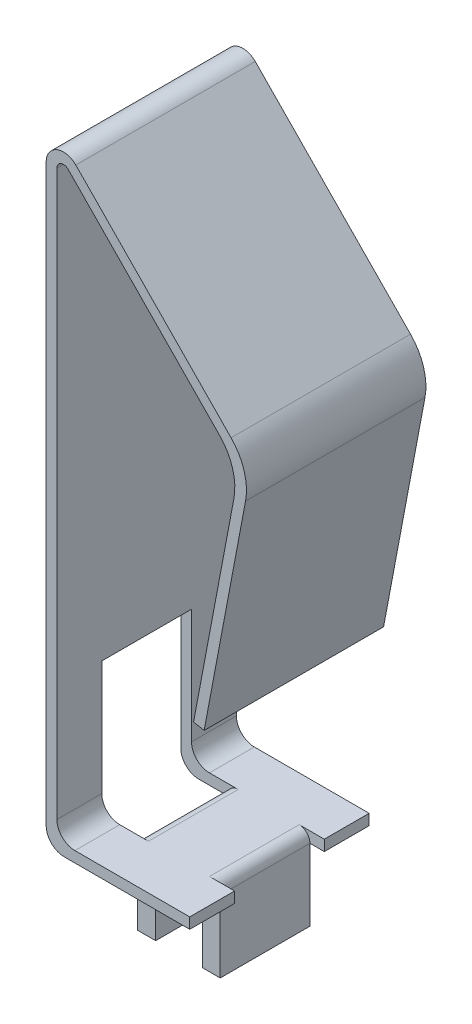
SolidWorks part; units mm, degrees
ref_plane "Plan de face" through (0, 0, 0) normal (0, 0, 1) x (1, 0, 0)
ref_plane "Plan de dessus" through (0, 0, 0) normal (0, 1, 0) x (1, 0, 0)
ref_plane "Plan de droite" through (0, 0, 0) normal (1, 0, 0) x (0, 0, -1)
sketch "Esquisse2" plane through (0, 0, 0) normal (0, 0, 1) x (1, 0, 0)
  line L0 (0, 0) -> (-3.7, 0)
  line L1 (-3.7, 0) -> (-3.7, 16.2178)
  line L2 (-3.3876, 16.3453) -> (1.3762, 11.4805)
  line L4 (0, 0) -> (0, -0.3)
  line L5 (0, -0.3) -> (-4, -0.3)
  line L6 (-4, -0.3) -> (-4, 16.2178)
  line L7 (-3.1733, 16.5552) -> (1.7, 11.5786)
  line L10 (-3.7, 0) -> (-4, 0) construction
  line L11 (-13.0232, 16.7) -> (-11.6924, 16.7) construction
  line L12 (-3.5866, 16.3865) -> (-3.7, 16.6643)
  line L13 (1.7, 11.5786) -> (0.402, 4.7)
  line L14 (0.1072, 4.7556) -> (1.3762, 11.4805)
  line L15 (0.1072, 4.7556) -> (0.402, 4.7)
  line L16 (1.3762, 11.4805) -> (1.5905, 11.6904) construction
  arc A0 (-4, 16.2178) -> (-3.1733, 16.5552) centre (-3.5178, 16.2178) cw
  arc A1 (-3.7, 16.2178) -> (-3.3876, 16.3453) centre (-3.5178, 16.2178) cw
  point P19 (-3.5178, 16.7)
  dimension "D2" = 17
  dimension "D4" = 12
  dimension "D1" = 0.3
  dimension "D3" = 4
  dimension "D5" = 7
  dimension "D6" = 5.7
extrude "Boss.-Extru.1" add sketch "Esquisse2" along normal blind 5 contours L6 A0 L7 L13 L15 L14 L2 A1 L1 L0 L4 L5
fillet "Congé2" radius 1.5 2 edges at (1.3762, 11.4805, 2.5) (1.7, 11.5786, 2.5)
fillet "Congé3" radius 0.5 2 edges at (-3.7, 0, 2.5) (-4, -0.3, 2.5)
sketch "Esquisse3" plane through (-4, 0, 0) normal (-1, 0, 0) x (0, 0, 1)
  line L0 (5, -0.3) -> (0, -0.3) construction
  line L1 (3.75, 3.7) -> (1.25, 3.7)
  line L2 (3.75, 3.7) -> (3.75, -0.3)
  line L3 (3.75, -0.3) -> (1.25, -0.3)
  line L4 (1.25, 3.7) -> (1.25, -0.3)
  point P6 (2.5, -0.3)
  point P7 (3.7358, 3.4905)
  dimension "D1" = 4
  dimension "D2" = 2.5
extrude "Enlèv. mat.-Extru.1" cut sketch "Esquisse3" against normal blind 1.3
sketch "Esquisse4" plane through (0, 0, 0) normal (1, 0, 0) x (0, 0, -1)
  line L0 (-5, 0) -> (0, 0) construction
  line L1 (-1.25, 0) -> (-3.75, 0)
  line L2 (-1.25, 0) -> (-1.25, -0.3)
  line L3 (-1.25, -0.3) -> (-3.75, -0.3)
  line L4 (-3.75, 0) -> (-3.75, -0.3)
  line L5 (-5, -0.3) -> (0, -0.3) construction
  line L6 (-3.75, 3.7) -> (-3.75, 0.5) construction
  line L7 (-1.25, 0.5) -> (-1.25, 3.7) construction
extrude "Enlèv. mat.-Extru.2" cut sketch "Esquisse4" against normal blind 0.4
ref_plane "Plan1" through (-1.55, 0, 0) normal (1, 0, 0) x (0, 0, -1)
sketch "Esquisse5" plane through (-0.4, 0, 0) normal (1, 0, 0) x (0, 0, -1)
  line L0 (-1.25, -0.3) -> (-3.75, -0.3) construction
  line L1 (-3.75, -0.3) -> (-1.25, -0.3)
  line L2 (-3.75, -0.3) -> (-3.75, -2.3)
  line L3 (-3.75, -2.3) -> (-1.25, -2.3)
  line L4 (-1.25, -0.3) -> (-1.25, -2.3)
  line L5 (-3.75, 0.5) -> (-3.75, 3.7) construction
  point P6 (-2.5, -0.3)
  point P7 (-6.047, -0.3)
  dimension "D1" = 2
extrude "Boss.-Extru.2" add sketch "Esquisse5" against normal blind 0.5
mirror "Symétrie1" about plane through (-1.55, 0, 0) normal (1, 0, 0) of "Boss.-Extru.2"
fillet "Congé4" radius 0.3 4 edges at (-0.4, 0, 2.5) (-2.7, 0, 2.5) (-0.9, -0.3, 2.5) (-2.2, -0.3, 2.5)
